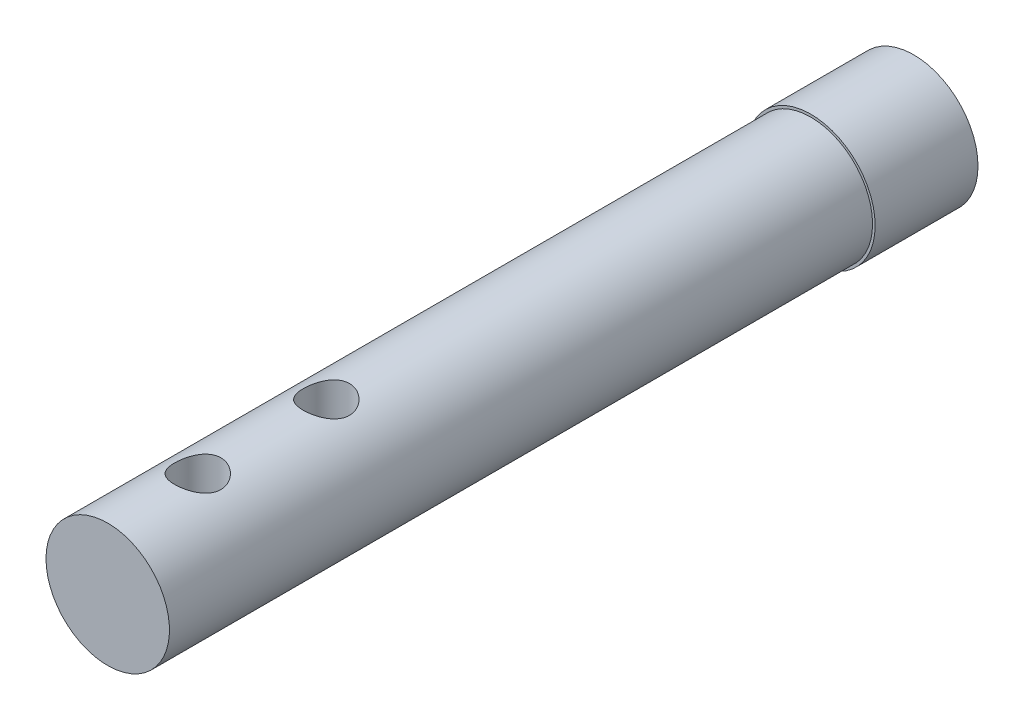
SolidWorks part; units mm, degrees
material "Galvanized Steel"
ref_plane "Front Plane" through (0, 0, 0) normal (0, 0, 1) x (1, 0, 0)
ref_plane "Top Plane" through (0, 0, 0) normal (0, 1, 0) x (1, 0, 0)
ref_plane "Right Plane" through (0, 0, 0) normal (1, 0, 0) x (0, 0, -1)
sketch "Sketch1" plane through (0, 0, 0) normal (0, 0, 1) x (1, 0, 0)
  circle A0 centre (0, 0) radius 10
  dimension "D1" = 20
extrude "Boss-Extrude1" add sketch "Sketch1" along normal blind 15
sketch "Sketch2" plane through (0, 0, 15) normal (0, 0, 1) x (1, 0, 0)
  circle A0 centre (0, 0) radius 12.5
  dimension "D1" = 25
extrude "Boss-Extrude2" add sketch "Sketch2" along normal blind 20
sketch "Sketch3" plane through (0, 0, 35) normal (0, 0, 1) x (1, 0, 0)
  circle A0 centre (0, 0) radius 12
  dimension "D1" = 24
extrude "Boss-Extrude3" add sketch "Sketch3" along normal blind 139.2
sketch "Sketch4" plane through (0, 0, 0) normal (0, 1, 0) x (1, 0, 0)
  line L0 (-12, -174.2) -> (12, -174.2) construction
  circle A0 centre (0, -154.2) radius 4.5
  dimension "D1" = 9
  dimension "D2" = 20
extrude "Cut-Extrude1" cut sketch "Sketch4" against normal through all both and the other way through all
sketch "Sketch5" plane through (0, 0, 0) normal (0, 1, 0) x (1, 0, 0)
  line L1 (12.5, -15) -> (-37.6297, -15)
  line L2 (12.5, -15) -> (12.5, 4.8742)
  line L3 (12.5, 4.8742) -> (-37.6297, 4.8742)
  line L4 (-37.6297, -15) -> (-37.6297, 4.8742)
extrude "Cut-Extrude2" cut sketch "Sketch5" against normal through all both and the other way through all
pattern_linear "LPattern1" count 2 spacing 25 along (0, 0, -1) of "Cut-Extrude1"
sketch "Sketch6" plane through (0, 0, 0) normal (0, 1, 0) x (1, 0, 0)
  line L1 (12, -174.2) -> (-23.8209, -174.2)
  line L2 (12, -174.2) -> (12, -171.7)
  line L3 (12, -171.7) -> (-23.8209, -171.7)
  line L4 (-23.8209, -174.2) -> (-23.8209, -171.7)
  line L5 (12, -174.2) -> (-23.8209, -171.7) construction
  line L6 (12, -171.7) -> (-23.8209, -174.2) construction
  point P4 (-5.9105, -172.95)
  dimension "D1" = 2.5
extrude "Cut-Extrude3" cut sketch "Sketch6" against normal through all both and the other way through all
